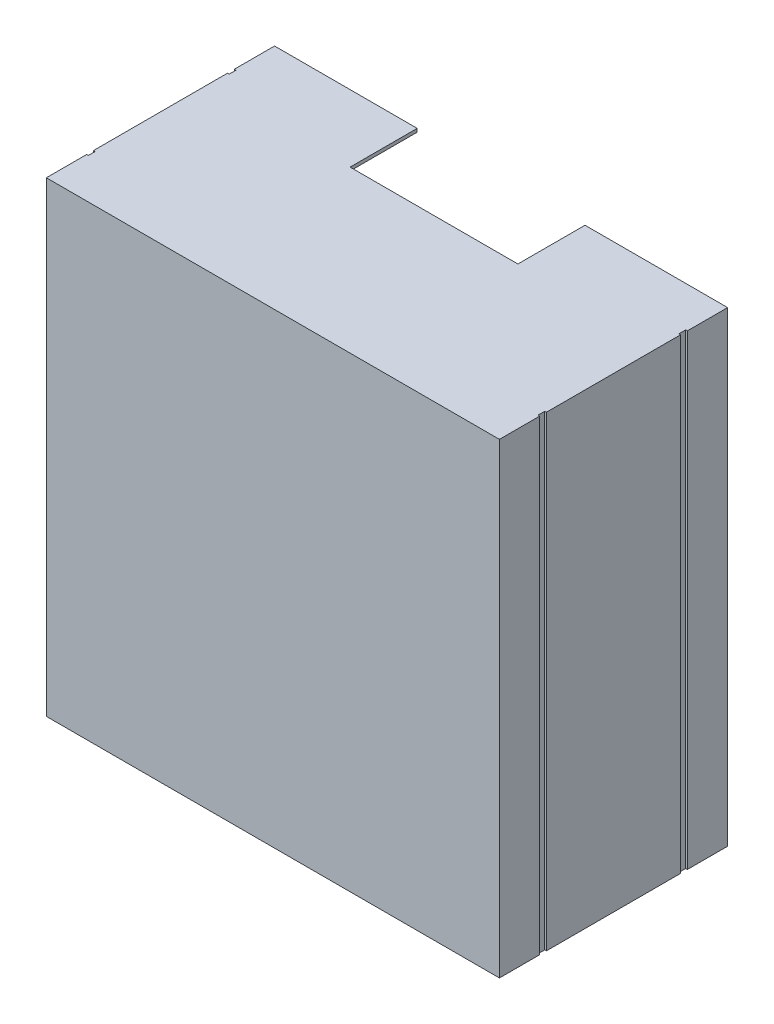
SolidWorks part; units mm, degrees
ref_plane "前视基准面" through (0, 0, 0) normal (0, 0, 1) x (1, 0, 0)
ref_plane "上视基准面" through (0, 0, 0) normal (0, 1, 0) x (1, 0, 0)
ref_plane "右视基准面" through (0, 0, 0) normal (1, 0, 0) x (0, 0, -1)
sketch "草图1" plane through (0, 0, 0) normal (0, 1, 0) x (1, 0, 0)
  line L1 (135, -68) -> (-135, -68)
  line L2 (135, -68) -> (135, 68)
  line L3 (135, 68) -> (-135, 68)
  line L4 (-135, -68) -> (-135, 68)
  line L5 (135, -68) -> (-135, 68) construction
  line L6 (135, 68) -> (-135, -68) construction
  point P0 (0, 0)
  dimension "D1" = 270
  dimension "D2" = 136
extrude "凸台-拉伸1" add sketch "草图1" along normal blind 278
sketch "草图2" plane through (0, 0, -68) normal (0, 0, -1) x (-1, 0, 0)
  line L14 (-133, 2) -> (133, 2)
  line L15 (133, 2) -> (133, 276)
  line L16 (133, 276) -> (-133, 276)
  line L17 (-133, 276) -> (-133, 2)
  line L18 (-133, 2) -> (133, 2)
  line L19 (133, 2) -> (133, 276)
  line L20 (133, 276) -> (-133, 276)
  line L21 (-133, 276) -> (-133, 2)
  dimension "D1" = 2
extrude "切除-拉伸1" cut sketch "草图2" against normal offset from surface (134 mm away) 2 up to face at (0, 139, 68)
sketch "草图3" plane through (0, 278, 0) normal (0, 1, 0) x (1, 0, 0)
  line L0 (0, 68) -> (0, -68) construction
  line L1 (135, 68) -> (-135, 68) construction
  line L2 (-135, -68) -> (135, -68) construction
  line L3 (50, 68) -> (-50, 68)
  line L4 (-50, 68) -> (-50, 28)
  line L5 (-50, 28) -> (50, 28)
  line L6 (50, 68) -> (50, 28)
  point P10 (0, 28)
  dimension "D1" = 40
  dimension "D2" = 100
extrude "切除-拉伸2" cut sketch "草图3" against normal up to next
sketch "草图4" plane through (0, 0, 0) normal (0, -1, 0) x (1, 0, 0)
  line L0 (0, 68) -> (0, -68) construction
  line L1 (-135, 68) -> (135, 68) construction
  line L2 (135, -68) -> (-135, -68) construction
  line L3 (-135, 0) -> (135, 0) construction
  line L4 (-135, -68) -> (-135, 68) construction
  line L5 (135, 68) -> (135, -68) construction
  line L6 (-135, 40) -> (-135, 44)
  line L7 (-135, 44) -> (-134, 44)
  line L8 (-134, 44) -> (-134, 40)
  line L9 (-134, 40) -> (-135, 40)
  line L10 (-134, -40) -> (-135, -40)
  line L11 (-134, -44) -> (-134, -40)
  line L12 (-135, -44) -> (-134, -44)
  line L13 (-135, -40) -> (-135, -44)
  line L14 (135, -40) -> (135, -44)
  line L15 (135, -44) -> (134, -44)
  line L16 (134, -44) -> (134, -40)
  line L17 (134, -40) -> (135, -40)
  line L18 (134, 40) -> (135, 40)
  line L19 (134, 44) -> (134, 40)
  line L20 (135, 44) -> (134, 44)
  line L21 (135, 40) -> (135, 44)
  dimension "D1" = 1
  dimension "D2" = 4
  dimension "D3" = 40
extrude "切除-拉伸3" cut sketch "草图4" against normal up to next
